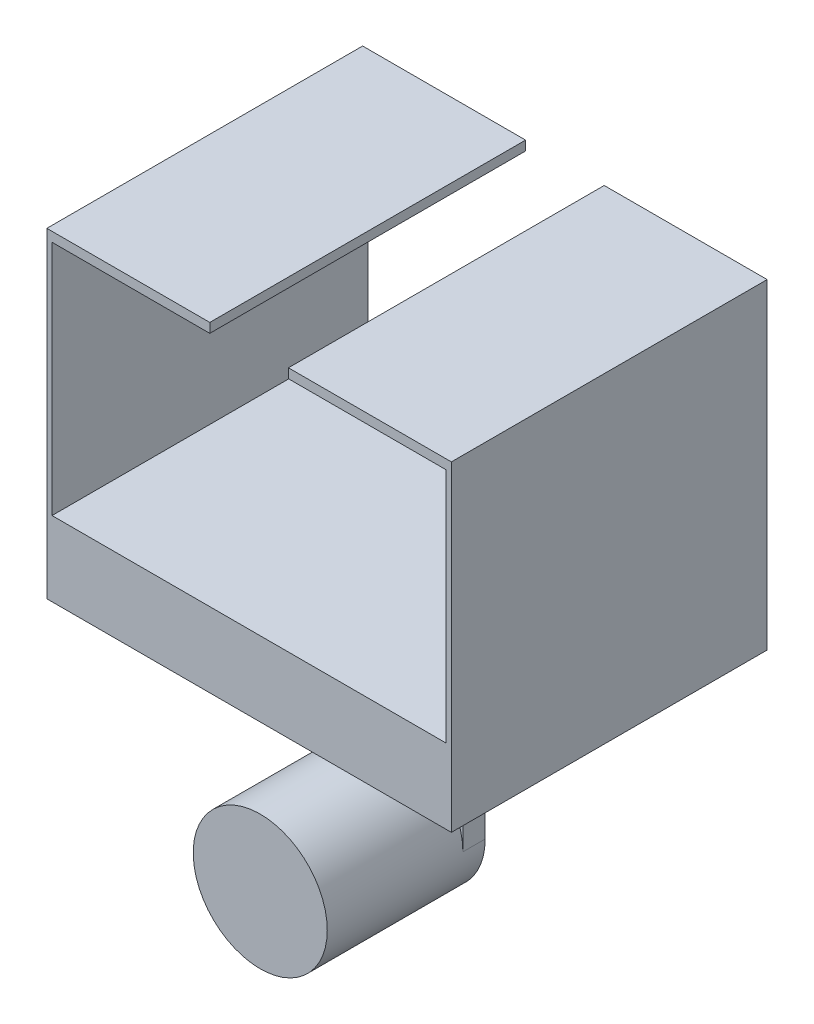
SolidWorks part; units mm, degrees
ref_plane "Front Plane" through (0, 0, 0) normal (0, 0, 1) x (1, 0, 0)
ref_plane "Top Plane" through (0, 0, 0) normal (0, 1, 0) x (1, 0, 0)
ref_plane "Right Plane" through (0, 0, 0) normal (1, 0, 0) x (0, 0, -1)
sketch "Sketch1" plane through (0, 0, 0) normal (0, 0, 1) x (1, 0, 0)
  circle A0 centre (0, 0) radius 10.7823
  dimension "D1" = 21.5646
extrude "Boss-Extrude1" add sketch "Sketch1" against normal blind 25.4
sketch "Sketch2" plane through (0, 0, -25.4) normal (0, 0, -1) x (-1, 0, 0)
  line L0 (-10.7823, 0) -> (10.7823, 0)
  line L1 (10.7823, 0) -> (10.7823, 25.4)
  line L2 (10.7823, 25.4) -> (-10.7823, 25.4)
  line L3 (-10.7823, 0) -> (-10.7823, 25.4)
  circle A0 centre (0, 0) radius 10.7823 construction
  dimension "D1" = 25.4
extrude "Boss-Extrude2" add sketch "Sketch2" against normal blind 3.5814
sketch "Sketch6" plane through (0, 25.4, 0) normal (0, 1, 0) x (1, 0, 0)
  line L0 (-10.7823, 23.6093) -> (10.7823, 23.6093) construction
  line L1 (-10.7823, 21.8186) -> (-10.7823, 25.4) construction
  line L2 (10.7823, 21.8186) -> (10.7823, 25.4) construction
  line L3 (0, 23.6093) -> (0, 25.4) construction
  line L6 (-10.7823, 25.4) -> (10.7823, 25.4) construction
  line L7 (-32.5374, 49.0093) -> (32.5374, 49.0093)
  line L8 (-32.5374, 49.0093) -> (-32.5374, -1.7907)
  line L9 (-32.5374, -1.7907) -> (32.5374, -1.7907)
  line L10 (32.5374, 49.0093) -> (32.5374, -1.7907)
  line L11 (0, 25.4) -> (0, 21.8186) construction
  line L12 (-10.7823, 21.8186) -> (10.7823, 21.8186) construction
  dimension "D1" = 50.8
  dimension "D2" = 65.0748
extrude "Boss-Extrude3" add sketch "Sketch6" along normal blind 51.6128
sketch "Sketch7" plane through (0, 0, 1.7907) normal (0, 0, 1) x (1, 0, 0)
  line L0 (-10.7823, 25.4) -> (10.7823, 25.4) construction
  line L1 (-31.7043, 37.4142) -> (31.7043, 37.4142)
  line L2 (-31.7043, 37.4142) -> (-31.7043, 75.4888)
  line L3 (-31.7043, 75.4888) -> (31.7043, 75.4888)
  line L4 (31.7043, 37.4142) -> (31.7043, 75.4888)
  line L5 (0, 77.0128) -> (0, 25.4) construction
  line L6 (-32.5374, 77.0128) -> (32.5374, 77.0128) construction
  line L7 (-32.5374, 25.4) -> (32.5374, 25.4) construction
  line L8 (-32.5374, 51.2064) -> (32.5374, 51.2064) construction
  line L9 (-32.5374, 77.0128) -> (-32.5374, 25.4) construction
  line L10 (32.5374, 77.0128) -> (32.5374, 25.4) construction
  dimension "D1" = 12.0142
  dimension "D2" = 63.4086
  dimension "D3" = 38.0746
extrude "Cut-Extrude1" cut sketch "Sketch7" against normal through all
sketch "Sketch8" plane through (0, 0, 1.7907) normal (0, 0, 1) x (1, 0, 0)
  line L0 (31.7043, 75.4888) -> (-31.7043, 75.4888) construction
  line L1 (-6.3246, 75.4888) -> (6.3246, 75.4888)
  line L2 (-6.3246, 75.4888) -> (-6.3246, 77.0128)
  line L3 (-6.3246, 77.0128) -> (6.3246, 77.0128)
  line L4 (6.3246, 75.4888) -> (6.3246, 77.0128)
  line L5 (-32.5374, 77.0128) -> (32.5374, 77.0128) construction
  line L6 (0, 37.4142) -> (0, 75.4888) construction
  line L7 (-31.7043, 37.4142) -> (31.7043, 37.4142) construction
  dimension "D2" = 12.6492
extrude "Cut-Extrude2" cut sketch "Sketch8" against normal through all
equation "\"F\"= 600'applied force (lbf)"
equation "\"SF\"= 4'Safety Factor"
equation "\"Sy\"= 40000'Yield Strength (PSI)"
equation "\"La\"= 1in'Feature A length"
equation "\"Ma\"= \"F\" * \"La\"'lbf in"
equation "\"Za\"= \"SF\" * \"Ma\" / \"Sy\"'Section Modulus (in^3)"
equation "\"ra\"= ( 4 * \"Za\" / pi ) ^ ( 1 / 3 )'RADIUS A"
equation "\"D\"= \"ra\" * 2'DIAMETER A"
equation "\"P_B\"= \"F\" * 2' FEATURE B AXIAL LOAD LBF"
equation "\"ALLOWSTRESS\"= \"Sy\" / \"SF\"'ALLOWABLE NORMAL STRESS"
equation "\"A_B\"= \"P_B\" / \"ALLOWSTRESS\"'FEATURE B REQUIRED AREA IN^2"
equation "\"T_B\"= \"A_B\" / \"D\"'FEATURE B REQUIRED THICKNESS"
equation "\"L_B\"= 1in'LENGTH OF B"
equation "\"L_C\"= \"A_FIT\" + \"B_FIT\" * 2'FEATURE C SPAN"
equation "\"B_C\" = 2in'BRACKET DEPTH"
equation "\"M_C\"= \"P_B\" * \"L_C\" / 4'MAX BENDING MOMENT"
equation "\"Z_C\"= \"M_C\" / \"ALLOWSTRESS\"'REQUIRED SECTION MODULUS IN^3"
equation "\"H_C\"= sqr ( 6 * \"Z_C\" / \"B_C\" )'required c thickness"
equation "\"P_D\"= \"F\"'FEATURE D AXIAL LOAD LBF"
equation "\"A_D\"= \"P_D\" / \"ALLOWSTRESS\"'FEATURE D REQUIRED AREA "
equation "\"P_E\"= \"F\"'E AXIAL LOAD LBF"
equation "\"A_E\"= \"P_E\" / \"ALLOWSTRESS\"'FEATURE E REQUIRED AREA"
equation "\"A_FIT\"= 0.498IN'T BEAM INTERFACE DIM A"
equation "\"B_FIT\" = 0.9992in'T BEAM INTERFACE DIM B"
equation "\"C_FIT\"= 1.499in'T BEAM INTERFACE DIM C"
equation "\"T_D\"= \"A_D\" / \"C_FIT\"'FEATURE D REQUIRED THIVKNESS"
equation "\"T_E\"= \"A_E\" / \"B_FIT\"'FEATURE E REQUIRED THICKNESS"
equation "\"OVERALLWIDTH\"= \"L_C\" + \"T_D\" * 2'SLECTED OVERALL BRACKET WIDTH"
equation "\"OVERALLHEIGHT\"= \"H_C\" + \"T_E\" + \"C_FIT\""
